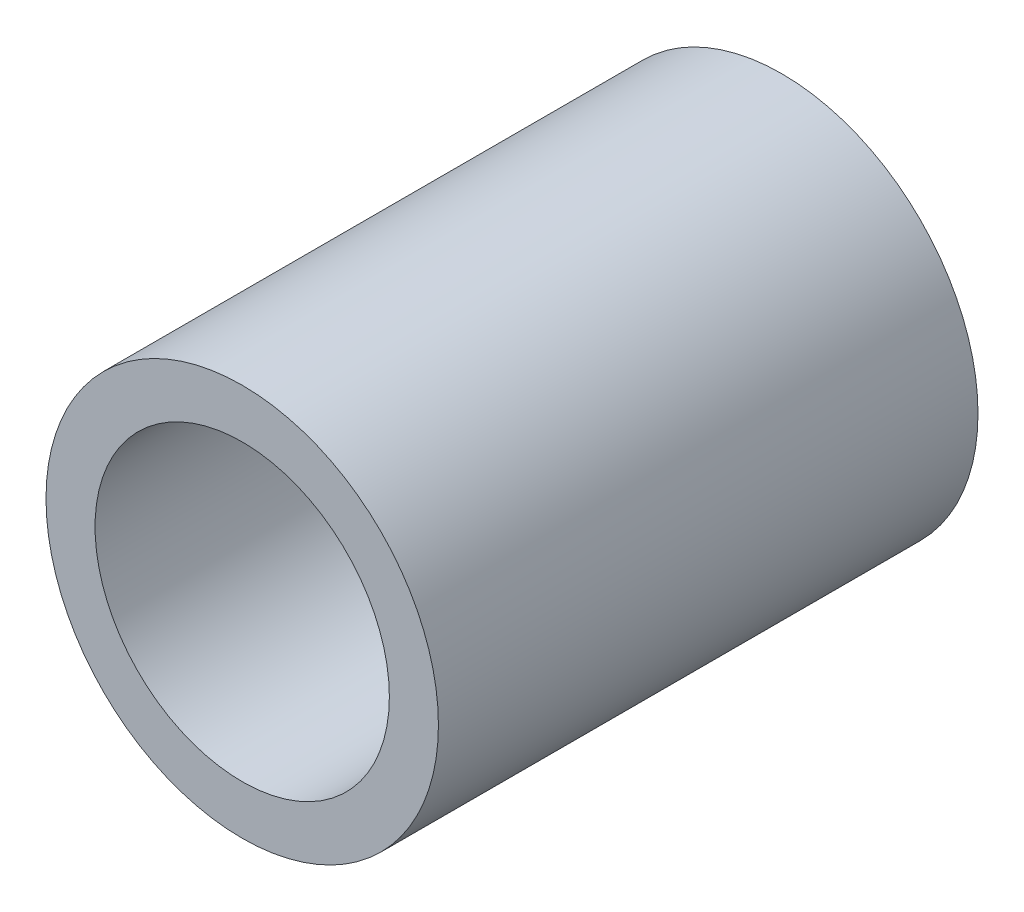
SolidWorks part; units mm, degrees
material "AISI 1020"
ref_plane "Ön Düzlem" through (0, 0, 0) normal (0, 0, 1) x (1, 0, 0)
ref_plane "Üst Düzlem" through (0, 0, 0) normal (0, 1, 0) x (1, 0, 0)
ref_plane "Sağ Düzlem" through (0, 0, 0) normal (1, 0, 0) x (0, 0, -1)
sketch "Çizim1" plane through (0, 0, 0) normal (0, 0, 1) x (1, 0, 0)
  circle A0 centre (0, 0) radius 30
  circle A1 centre (0, 0) radius 40
  dimension "D1" = 60
  dimension "D2" = 80
extrude "Yükseklik-Ekstrüzyon1" add sketch "Çizim1" along normal blind 110
